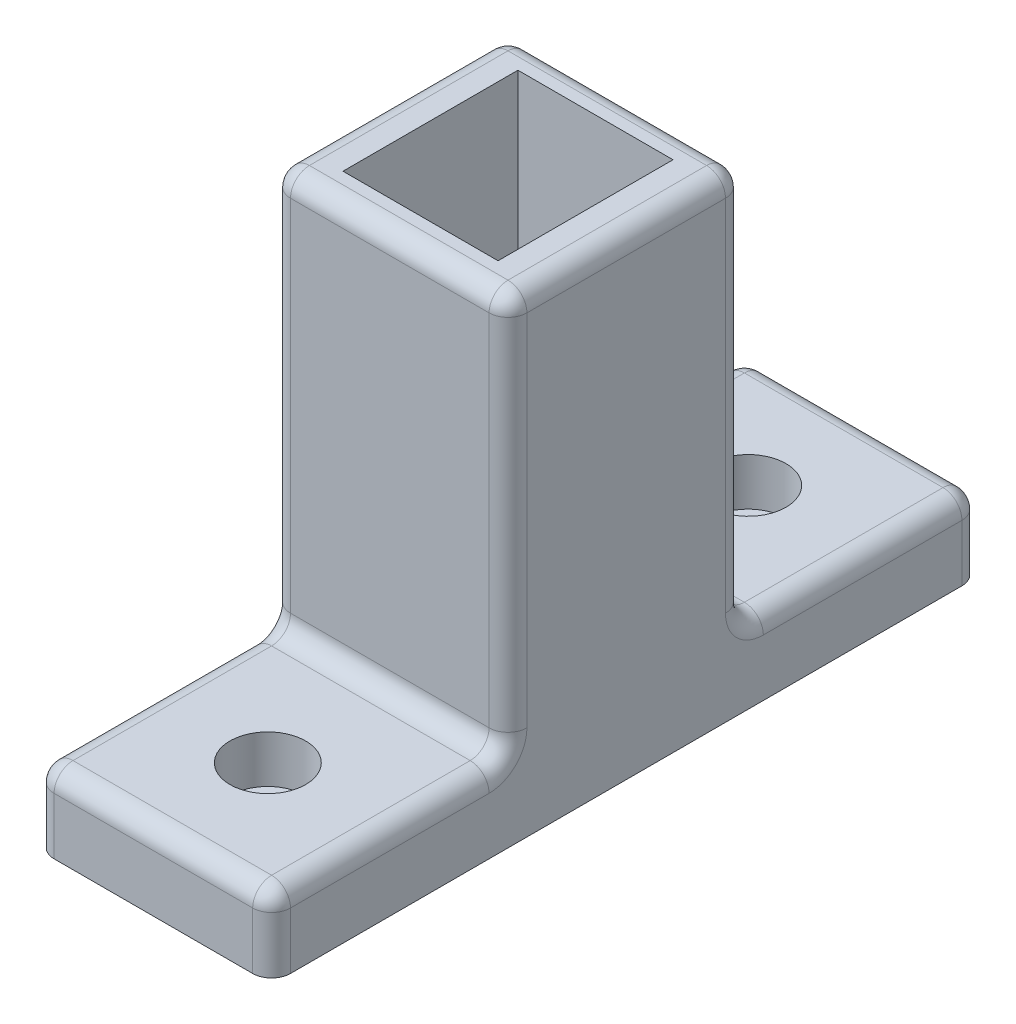
SolidWorks part; units mm, degrees
material "ABS"
ref_plane "Front Plane" through (0, 0, 0) normal (0, 0, 1) x (1, 0, 0)
ref_plane "Top Plane" through (0, 0, 0) normal (0, 1, 0) x (1, 0, 0)
ref_plane "Right Plane" through (0, 0, 0) normal (1, 0, 0) x (0, 0, -1)
sketch "Sketch1" plane through (0, 0, 0) normal (0, 1, 0) x (1, 0, 0)
  line L1 (-8.2, -9.25) -> (8.2, -9.25)
  line L2 (-8.2, -9.25) -> (-8.2, 9.25)
  line L3 (-8.2, 9.25) -> (8.2, 9.25)
  line L4 (8.2, -9.25) -> (8.2, 9.25)
  line L5 (-8.2, -9.25) -> (8.2, 9.25) construction
  line L6 (-8.2, 9.25) -> (8.2, -9.25) construction
  line L7 (-12.5, -12.5) -> (12.5, -12.5)
  line L8 (-12.5, -12.5) -> (-12.5, 12.5)
  line L9 (-12.5, 12.5) -> (12.5, 12.5)
  line L10 (12.5, -12.5) -> (12.5, 12.5)
  line L11 (-12.5, -12.5) -> (12.5, 12.5) construction
  line L12 (-12.5, 12.5) -> (12.5, -12.5) construction
  point P0 (0, 0)
  point P6 (0, 0)
  dimension "D1" = 16.4
  dimension "D2" = 18.5
  dimension "D3" = 25
  dimension "D4" = 25
extrude "Boss-Extrude1" add sketch "Sketch1" along normal blind 50
sketch "Sketch6" plane through (0, 0, 0) normal (0, 1, 0) x (1, 0, 0)
  line L13 (-12.5, -37.5) -> (12.5, -37.5)
  line L14 (-12.5, -37.5) -> (-12.5, 37.5)
  line L15 (-12.5, 37.5) -> (12.5, 37.5)
  line L16 (12.5, -37.5) -> (12.5, 37.5)
  line L17 (-12.5, -37.5) -> (12.5, 37.5) construction
  line L18 (-12.5, 37.5) -> (12.5, -37.5) construction
  point P4 (0, 0)
  dimension "D5" = 75
  dimension "D6" = 25
extrude "Boss-Extrude3" add sketch "Sketch6" along normal blind 8
fillet "Fillet2" radius 2 20 edges at (0, 8, -12.5) (0, 50, -12.5) (12.5, 29, -12.5) (12.5, 50, 0) (12.5, 29, 12.5) (-12.5, 29, 12.5) (0, 50, 12.5) (-12.5, 29, -12.5) (-12.5, 50, 0) (-12.5, 8, -25) (12.5, 8, -25) (0, 8, -37.5) (0, 8, 37.5) (-12.5, 8, 25) (0, 8, 12.5) (12.5, 8, 25) (12.5, 4, -37.5) (-12.5, 4, -37.5) (12.5, 4, 37.5) (-12.5, 4, 37.5)
sketch "Sketch7" plane through (0, 8, 0) normal (0, 1, 0) x (1, 0, 0)
  line L0 (0, 0) -> (0, 25.4) construction
  line L1 (0, 0) -> (0, -25.4) construction
  circle A0 centre (0, 0) radius 4
  circle A1 centre (0, 25.4) radius 4
  circle A2 centre (0, -25.4) radius 4
extrude "Cut-Extrude1" cut sketch "Sketch7" against normal blind 5
sketch "Sketch8" plane through (0, 0, 0) normal (0, 1, 0) x (1, 0, 0)
  line L0 (0, 0) -> (0, 25.4) construction
  line L1 (0, 0) -> (0, -25.4) construction
  circle A0 centre (0, 0) radius 2.3813
  circle A1 centre (0, 25.4) radius 2.3813
  circle A2 centre (0, -25.4) radius 2.3813
extrude "Cut-Extrude4" cut sketch "Sketch8" against normal through all and the other way through all
